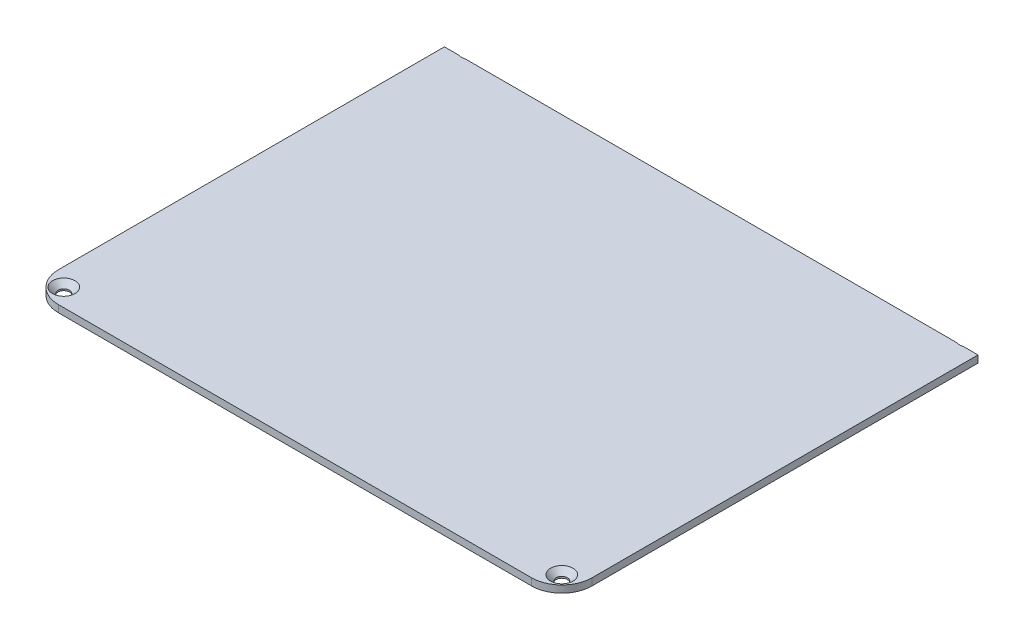
SolidWorks part; units mm, degrees
ref_plane "Ebene vorne" through (0, 0, 0) normal (0, 0, 1) x (1, 0, 0)
ref_plane "Ebene oben" through (0, 0, 0) normal (0, 1, 0) x (1, 0, 0)
ref_plane "Ebene rechts" through (0, 0, 0) normal (1, 0, 0) x (0, 0, -1)
sketch "Skizze1" plane through (0, 0, 0) normal (0, 1, 0) x (1, 0, 0)
  line L1 (0, 0) -> (300, 0)
  line L2 (0, 0) -> (0, 234)
  line L3 (0, 234) -> (300, 234)
  line L4 (300, 0) -> (300, 234)
  dimension "D1" = 234
  dimension "D2" = 300
extrude "Aufsatz-Linear austragen1" add sketch "Skizze1" along normal blind 4
fillet "Verrundung1" radius 17 2 edges at (300, 2, 0) (0, 2, 0)
hole_wizard "Formsenkung für M6 Senkschraube mit Schlitz/Kreuzschlitz1" positions "Skizze3" profile "Skizze2" countersink size "M6" standard "DIN" end condition through all
sketch "Skizze3" plane through (0, 4, 0) normal (0, 1, 0) x (1, 0, 0)
  line L0 (0, 234) -> (0, 17) construction
  line L1 (17, 0) -> (283, 0) construction
  line L2 (300, 17) -> (300, 234) construction
  point P0 (10, 10)
  point P2 (290, 10)
  point P4 (290, 240)
  point P6 (10, 240)
  dimension "D1" = 10
  dimension "D2" = 10
  dimension "D3" = 10
  dimension "D4" = 230
sketch "Skizze2" plane through (10, 4, -10) normal (1, 0, 0) x (0, 0, 1)
  line L0 (0, 0) -> (0, 4)
  line L1 (0, 4) -> (3.2, 4)
  line L2 (3.2, 4) -> (3.2, 3.1)
  line L3 (3.2, 3.1) -> (6.3, 0)
  line L5 (6.3, 0) -> (0, 0)
  line L6 (-3.2, 3.1) -> (-6.3, 0) construction
  line L11 (0, -6.35) -> (0, 107.95) construction
  dimension "Bohrerdurchmesser" = 6.4
  dimension "Bohrungstiefe" = 4
  dimension "Senkdurchmesser (Oben)" = 12.6
  dimension "Senkwinkel (Oben)" = 90
